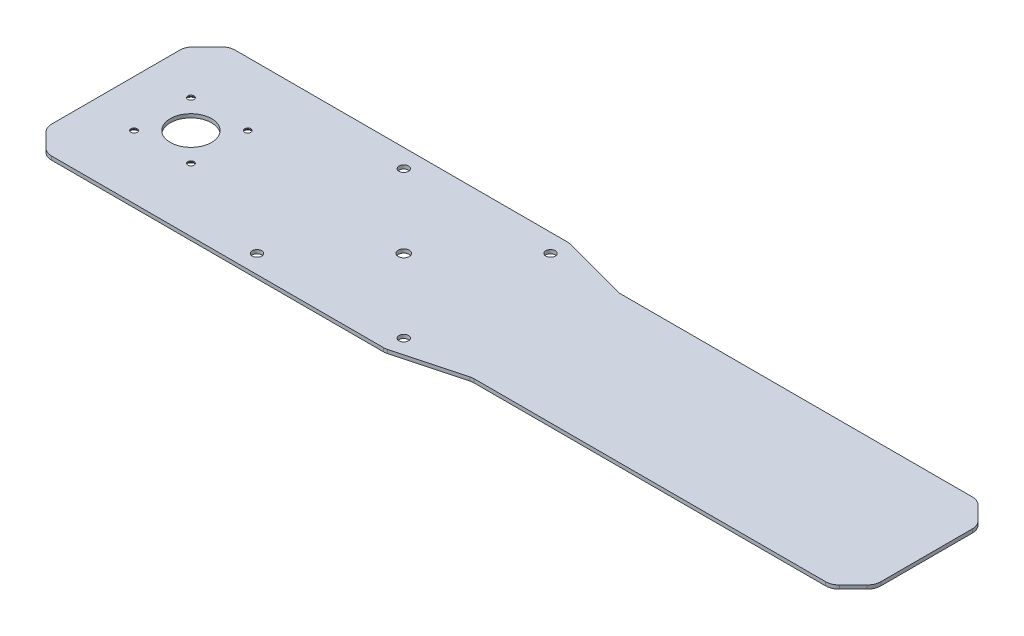
SolidWorks part; units mm, degrees
material "1060 Alloy"
ref_plane "Front Plane" through (0, 0, 0) normal (0, 0, 1) x (1, 0, 0)
ref_plane "Top Plane" through (0, 0, 0) normal (0, 1, 0) x (1, 0, 0)
ref_plane "Right Plane" through (0, 0, 0) normal (1, 0, 0) x (0, 0, -1)
sketch "Sketch1" plane through (0, 0, 0) normal (0, 1, 0) x (1, 0, 0)
  line L0 (40, -50) -> (77.3205, -40)
  line L1 (-40, 50) -> (40, 50)
  line L2 (-40, 50) -> (-40, -50) construction
  line L3 (-40, -50) -> (40, -50)
  line L4 (40, 50) -> (40, -50) construction
  line L5 (-40, 50) -> (40, -50) construction
  line L6 (-40, -50) -> (40, 50) construction
  line L7 (-40, 50) -> (-157, 50)
  line L8 (-40, 50) -> (-40, -50) construction
  line L9 (-40, -50) -> (-157, -50)
  line L10 (-157, 50) -> (-157, -50)
  line L12 (40, 50) -> (40, -50) construction
  line L14 (40, 50) -> (77.3205, 40)
  line L16 (77.3205, 40) -> (285, 40)
  line L17 (77.3205, 40) -> (77.3205, -40) construction
  line L18 (77.3205, -40) -> (285, -40)
  line L19 (285, 40) -> (285, -40)
  point P0 (0, 0)
  point P11 (250, 0)
  dimension "D1" = 80
  dimension "D2" = 100
  dimension "D5" = 250
  dimension "D4" = 75
  dimension "D6" = 75
  dimension "D7" = 80
  dimension "D8" = 35
  dimension "D3" = 117
extrude "Boss-Extrude2" add sketch "Sketch1" along normal blind 2
chamfer "Chamfer2" distance 12 angle 45 4 edges at (-157, 1, 50) (-157, 1, -50) (285, 1, -40) (285, 1, 40)
fillet "Fillet1" radius 7.5 12 edges at (-145, 1, -50) (-157, 1, -38) (-157, 1, 38) (-145, 1, 50) (273, 1, 40) (285, 1, 28) (285, 1, -28) (273, 1, -40) (40, 1, 50) (77.3205, 1, 40) (77.3205, 1, -40) (40, 1, -50)
sketch "Sketch2" plane through (0, 2, 0) normal (0, 1, 0) x (1, 0, 0)
  line L0 (0, 50) -> (0, -50) construction
  line L1 (39.0126, 50) -> (-141.8934, 50) construction
  line L2 (-141.8934, -50) -> (39.0126, -50) construction
  line L3 (-157, 0) -> (285, 0) construction
  line L4 (-157, 34.8934) -> (-157, -34.8934) construction
  line L5 (285, -24.8934) -> (285, 24.8934) construction
  circle A0 centre (-40, 40) radius 2.575
  circle A1 centre (40, 40) radius 2.575
  circle A2 centre (40, -40) radius 2.575
  circle A3 centre (-40, -40) radius 2.575
  circle A4 centre (-116, 0) radius 11.25
  circle A5 centre (0, 0) radius 3
  dimension "D3" = 5.15
  dimension "D4" = 22.5
  dimension "D6" = 6
  dimension "D1" = 40
  dimension "D2" = 40
  dimension "D5" = 41
extrude "Cut-Extrude1" cut sketch "Sketch2" against normal through all
hole_wizard "CSK for M3 Countersunk Flat Head Screw2" positions "Sketch5" profile "Sketch4" countersink size "M3" standard "DIN" end condition through all
sketch "Sketch5" plane through (0, 0, 0) normal (0, -1, 0) x (-1, 0, 0)
  line L0 (157, 0) -> (0, 0) construction
  line L1 (157, 34.8934) -> (157, -34.8934) construction
  line L3 (116, -50) -> (116, 50) construction
  line L4 (141.8934, -50) -> (-39.0126, -50) construction
  line L5 (-39.0126, 50) -> (141.8934, 50) construction
  point P16 (131.5, -15.5)
  point P22 (100.5, -15.5)
  point P23 (100.5, 15.5)
  point P24 (131.5, 15.5)
  dimension "D5" = 41
  dimension "D3" = 15.5
  dimension "D7" = 31
  dimension "D6" = 31
  dimension "D4" = 15.5
  dimension "D1" = 2
  dimension "D2" = 2
sketch "Sketch4" plane through (-131.5, 0, -15.5) normal (1, 0, 0) x (0, 0, -1)
  line L0 (0, 0) -> (0, 2)
  line L1 (0, 2) -> (1.7, 2)
  line L2 (1.7, 2) -> (1.7, 1.45)
  line L3 (1.7, 1.45) -> (3.15, 0)
  line L5 (3.15, 0) -> (0, 0)
  line L6 (-1.7, 1.45) -> (-3.15, 0) construction
  line L11 (0, -6.35) -> (0, 107.95) construction
  dimension "Thru Hole Dia." = 3.4
  dimension "Thru Hole Depth" = 2
  dimension "Near C'Sink Dia." = 6.3
  dimension "Near C'Sink Angle" = 90
equation "\"Elevator Guide Rod Distance\"= 80mm"
equation "\"Extra Spacing\"= 20mm"
equation "\"Plate Thickness\"= 2mm"
equation "\"D1@Sketch1\"=\"Elevator Guide Rod Distance\""
equation "\"D2@Sketch1\"=\"Elevator Guide Rod Distance\"+\"Extra Spacing\""
equation "\"Elevator Servo Offset\"= 75mm"
equation "\"Servo Width\"= 42mm"
equation "\"Pivot Point End Offset\"= 35mm"
equation "\"Origin Pivot Distance\"= 250mm"
equation "\"D5@Sketch1\"=\"Origin Pivot Distance\""
equation "\"Narrow Section Width\"= 80mm"
equation "\"D7@Sketch1\"=\"Narrow Section Width\""
equation "\"D8@Sketch1\"=\"Pivot Point End Offset\""
equation "\"D1@Sketch2\"=\"Elevator Guide Rod Distance\"/2"
equation "\"D2@Sketch2\"=\"Elevator Guide Rod Distance\"/2"
equation "\"Guide Rod Diameter\"= 5mm"
equation "\"D3@Sketch2\"=\"Guide Rod Diameter\"+.15"
equation "\"Servo Hole X-Offset\"= 15.5mm"
equation "\"Servo Hole Y-Offset\"= 15.5mm"
equation "\"D1\"= \"Servo Width\" / 2 + \"Extra Spacing\""
equation "\"D3@Sketch5\"=\"Servo Hole Y-Offset\""
equation "\"D5@Sketch5\"=\"Servo Width\"/2 + \"Extra Spacing\""
equation "\"D7@Sketch5\"=\"Servo Hole Y-Offset\"*2"
equation "\"D6@Sketch5\"=\"Servo Hole X-Offset\"*2 "
equation "\"D4@Sketch5\"=\"Servo Hole X-Offset\""
equation "\"Servo Shaft Diameter\"= 22.5mm"
equation "\"D5@Sketch2\"=\"Servo Width\" / 2 + \"Extra Spacing\""
equation "\"D4@Sketch2\"=\"Servo Shaft Diameter\""
equation "\"Elevator Screw Lift Diameter\"= 6mm"
equation "\"D6@Sketch2\"=\"Elevator Screw Lift Diameter\""
equation "\"D3@Sketch1\"=\"Servo Width\" + \"Extra Spacing\" * 2 + 35"
equation "\"D1@Boss-Extrude2\"=\"Plate Thickness\""
